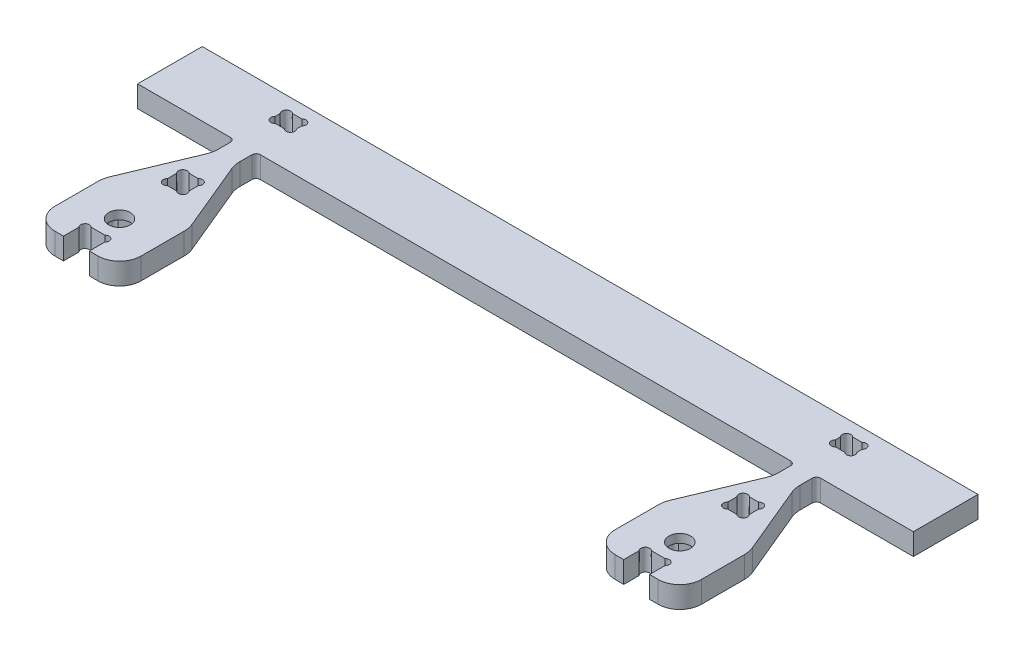
SolidWorks part; units mm, degrees
ref_plane "정면" through (0, 0, 0) normal (0, 0, 1) x (1, 0, 0)
ref_plane "윗면" through (0, 0, 0) normal (0, 1, 0) x (1, 0, 0)
ref_plane "우측면" through (0, 0, 0) normal (1, 0, 0) x (0, 0, -1)
sketch "스케치1" plane through (0, 0, 0) normal (0, 1, 0) x (1, 0, 0)
  line L0 (0, 0) -> (0, 54.2) construction
  line L1 (-90, 54.2) -> (90, 54.2)
  line L2 (90, 54.2) -> (90, 39.2)
  line L3 (90, 39.2) -> (75, 39.2)
  line L4 (75, 39.2) -> (75, 0)
  line L5 (75, 0) -> (55, 0)
  line L6 (55, 0) -> (55, 39.2)
  line L7 (55, 39.2) -> (-55, 39.2)
  line L8 (75, 39.2) -> (55, 39.2) construction
  line L9 (55, 0) -> (0, 0) construction
  line L10 (75, 10) -> (65, 10) construction
  line L11 (65, 10) -> (55, 10) construction
  line L12 (65, 10) -> (65, 0) construction
  line L13 (-65, 10) -> (-65, 0) construction
  line L14 (-65, 10) -> (-55, 10) construction
  line L15 (-75, 10) -> (-65, 10) construction
  line L16 (-75, 39.2) -> (-55, 39.2) construction
  line L17 (-55, 0) -> (-55, 39.2)
  line L18 (-75, 0) -> (-55, 0)
  line L19 (-75, 39.2) -> (-75, 0)
  line L20 (-90, 39.2) -> (-75, 39.2)
  line L21 (-90, 54.2) -> (-90, 39.2)
  circle A0 centre (65, 10) radius 2.5
  circle A1 centre (-65, 10) radius 2.5
  point P16 (0, 39.2)
  dimension "D1" = 5
  dimension "D2" = 65
  dimension "D3" = 39.2
  dimension "D4" = 90
  dimension "D5" = 15
  dimension "D6" = 20
extrude "보스-돌출1" add sketch "스케치1" along normal blind 5
sketch "스케치2" plane through (0, 5, 0) normal (0, 1, 0) x (1, 0, 0)
  line L0 (67.5, 52.6142) -> (67.5, 54.2) construction
  line L1 (75, 39.2) -> (67.5, 39.2)
  line L2 (75, 39.2) -> (75, 35.2)
  line L3 (75, 35.2) -> (67.5, 35.2)
  line L4 (67.5, 39.2) -> (67.5, 35.2)
  line L5 (-67.5, 52.6142) -> (-67.5, 54.2) construction
  line L6 (-75, 39.2) -> (-67.5, 39.2)
  line L7 (-75, 39.2) -> (-75, 35.2)
  line L8 (-75, 35.2) -> (-67.5, 35.2)
  line L9 (-67.5, 39.2) -> (-67.5, 35.2)
  dimension "D1" = 4
extrude "컷-돌출1" [suppressed] cut sketch "스케치2" against normal blind 10
sketch "스케치4" plane through (0, 0, 0) normal (0, -1, 0) x (1, 0, 0)
  line L0 (0, 0) -> (0, -39.2) construction
  line L1 (-55, -39.2) -> (55, -39.2) construction
  line L2 (65, -10) -> (65, -17) construction
  line L3 (-65, -10) -> (-65, -17) construction
  circle A0 centre (65, -10) radius 7 construction
  circle A1 centre (65, -17) radius 1.1
  circle A2 centre (58.9378, -6.5) radius 1.1
  circle A3 centre (71.0622, -6.5) radius 1.1
  circle A5 centre (-65, -10) radius 7 construction
  circle A6 centre (-71.0622, -6.5) radius 1.1
  circle A7 centre (-58.9378, -6.5) radius 1.1
  circle A8 centre (-65, -17) radius 1.1
  point P11 (65, -10)
  point P20 (65, -10)
  dimension "D1" = 2.2
  dimension "D2" = 14
  dimension "D3" = 3
extrude "컷-돌출3" [suppressed] cut sketch "스케치4" against normal blind 10
fillet "필렛1" radius 5 4 edges at (-75, 2.5, 0) (-55, 2.5, 0) (55, 2.5, 0) (75, 2.5, 0)
sketch "스케치6" plane through (0, 0, 0) normal (0, -1, 0) x (1, 0, 0)
  line L0 (60, 0) -> (70, 0) construction
  line L1 (62, 0) -> (68, 0)
  line L2 (62, 0) -> (62, -5)
  line L3 (62, -5) -> (68, -5)
  line L4 (68, 0) -> (68, -5)
  line L5 (0, 0) -> (0, -39.2) construction
  line L6 (-55, -39.2) -> (55, -39.2) construction
  line L7 (-68, 0) -> (-68, -5)
  line L8 (-62, -5) -> (-68, -5)
  line L9 (-62, 0) -> (-62, -5)
  line L10 (-62, 0) -> (-68, 0)
  dimension "D1" = 5
extrude "컷-돌출5" cut sketch "스케치6" against normal blind 10
sketch "스케치7" plane through (0, 0, 0) normal (0, -1, 0) x (1, 0, 0)
  line L0 (62, -5) -> (62.7071, -4.2929) construction
  line L1 (68, -5) -> (67.2929, -4.2929) construction
  line L2 (62, -5) -> (68, -5) construction
  line L3 (62, -5) -> (68, -5) construction
  line L4 (0, 0) -> (0, -39.2) construction
  line L5 (-55, -39.2) -> (55, -39.2) construction
  line L6 (-68, -5) -> (-67.2929, -4.2929) construction
  line L7 (-62, -5) -> (-62.7071, -4.2929) construction
  circle A0 centre (62.7071, -4.2929) radius 1
  circle A1 centre (67.2929, -4.2929) radius 1
  circle A2 centre (-67.2929, -4.2929) radius 1
  circle A3 centre (-62.7071, -4.2929) radius 1
  dimension "D3" = 2
  dimension "D1" = 45
  dimension "D2" = 45
extrude "컷-돌출6" cut sketch "스케치7" against normal blind 10
sketch "스케치8" plane through (0, 5, 0) normal (0, 1, 0) x (1, 0, 0)
  line L0 (67.5, 39.2) -> (62.5, 39.2) construction
  line L1 (75, 39.2) -> (67.5, 39.2)
  line L2 (75, 39.2) -> (75, 34.2)
  line L3 (75, 34.2) -> (67.5, 34.2)
  line L4 (67.5, 39.2) -> (67.5, 34.2)
  line L5 (55, 39.2) -> (62.5, 39.2)
  line L6 (55, 39.2) -> (55, 34.2)
  line L7 (55, 34.2) -> (62.5, 34.2)
  line L8 (62.5, 39.2) -> (62.5, 34.2)
  line L9 (62.5, 34.2) -> (67.5, 34.2) construction
  line L10 (0, 0) -> (0, 39.2) construction
  line L11 (-55, 39.2) -> (55, 39.2) construction
  line L12 (-62.5, 34.2) -> (-67.5, 34.2) construction
  line L13 (-67.5, 39.2) -> (-62.5, 39.2) construction
  line L14 (-62.5, 39.2) -> (-62.5, 34.2)
  line L15 (-55, 34.2) -> (-62.5, 34.2)
  line L16 (-55, 39.2) -> (-55, 34.2)
  line L17 (-55, 39.2) -> (-62.5, 39.2)
  line L18 (-67.5, 39.2) -> (-67.5, 34.2)
  line L19 (-75, 34.2) -> (-67.5, 34.2)
  line L20 (-75, 39.2) -> (-75, 34.2)
  line L21 (-75, 39.2) -> (-67.5, 39.2)
  dimension "D1" = 5
  dimension "D2" = 5
extrude "컷-돌출7" cut sketch "스케치8" against normal blind 10
fillet "필렛2" radius 1 4 edges at (-67.5, 2.5, -39.2) (-62.5, 2.5, -39.2) (62.5, 2.5, -39.2) (67.5, 2.5, -39.2)
sketch "스케치10" plane through (0, 5, 0) normal (0, 1, 0) x (1, 0, 0)
  line L0 (75, 16.2) -> (55, 16.2) construction
  line L2 (75, 5) -> (75, 34.2) construction
  line L3 (75, 34.2) -> (67.5, 34.2)
  line L4 (62.5, 34.2) -> (55, 34.2)
  line L5 (55, 34.2) -> (55, 5) construction
  line L6 (0, 0) -> (0, 39.2) construction
  line L7 (-61.5, 39.2) -> (61.5, 39.2) construction
  line L8 (62.5, 34.2) -> (55, 16.2)
  line L9 (55, 16.2) -> (55, 34.2)
  line L10 (67.5, 34.2) -> (75, 16.2)
  line L11 (75, 16.2) -> (75, 34.2)
  line L12 (-75, 16.2) -> (-55, 16.2) construction
  line L13 (-75, 16.2) -> (-75, 34.2)
  line L14 (-67.5, 34.2) -> (-75, 16.2)
  line L15 (-55, 16.2) -> (-55, 34.2)
  line L16 (-62.5, 34.2) -> (-55, 16.2)
  line L17 (-62.5, 34.2) -> (-55, 34.2)
  line L18 (-75, 34.2) -> (-67.5, 34.2)
  dimension "D1" = 18
extrude "컷-돌출9" cut sketch "스케치10" against normal blind 10
fillet "필렛3" radius 6 8 edges at (-55, 2.5, -16.2) (-75, 2.5, -16.2) (55, 2.5, -16.2) (75, 2.5, -16.2) (-67.5, 2.5, -34.2) (-62.5, 2.5, -34.2) (62.5, 2.5, -34.2) (67.5, 2.5, -34.2)
sketch "스케치12" plane through (0, 5, 0) normal (0, 1, 0) x (1, 0, 0)
  line L0 (0, 0) -> (0, 39.2) construction
  line L1 (62.5, 47.2) -> (67.5, 47.2)
  line L2 (62.5, 47.2) -> (62.5, 51.2)
  line L3 (62.5, 51.2) -> (67.5, 51.2)
  line L4 (67.5, 47.2) -> (67.5, 51.2)
  line L5 (62.5, 27.2) -> (67.5, 27.2)
  line L6 (62.5, 27.2) -> (62.5, 22.2)
  line L7 (62.5, 22.2) -> (67.5, 22.2)
  line L8 (67.5, 27.2) -> (67.5, 22.2)
  line L9 (-61.5, 39.2) -> (61.5, 39.2) construction
  line L10 (-67.5, 27.2) -> (-67.5, 22.2)
  line L11 (-62.5, 22.2) -> (-67.5, 22.2)
  line L12 (-62.5, 27.2) -> (-62.5, 22.2)
  line L13 (-62.5, 27.2) -> (-67.5, 27.2)
  line L14 (-67.5, 47.2) -> (-67.5, 51.2)
  line L15 (-62.5, 51.2) -> (-67.5, 51.2)
  line L16 (-62.5, 47.2) -> (-62.5, 51.2)
  line L17 (-62.5, 47.2) -> (-67.5, 47.2)
  line L18 (90, 54.2) -> (-90, 54.2) construction
  line L19 (62.5, 36.8) -> (67.5, 36.8) construction
  line L20 (62.5, 38.2) -> (62.5, 35.4) construction
  line L21 (67.5, 35.4) -> (67.5, 38.2) construction
  line L22 (65, 36.8) -> (65, 47.2) construction
  line L23 (65, 36.8) -> (65, 27.2) construction
  dimension "D1" = 3
  dimension "D2" = 4
  dimension "D3" = 20
  dimension "D4" = 5
  dimension "D5" = 5
extrude "컷-돌출10" cut sketch "스케치12" against normal blind 5
sketch "스케치14" plane through (0, 0, 0) normal (0, -1, 0) x (-1, 0, 0)
  line L1 (-65, 14.6188) -> (-69, 12.3094)
  line L2 (-69, 12.3094) -> (-69, 7.6906)
  line L3 (-69, 7.6906) -> (-65, 5.3812)
  line L4 (-65, 5.3812) -> (-61, 7.6906)
  line L5 (-61, 7.6906) -> (-61, 12.3094)
  line L6 (-61, 12.3094) -> (-65, 14.6188)
  line L7 (65, 14.6188) -> (61, 12.3094)
  line L8 (61, 12.3094) -> (61, 7.6906)
  line L9 (61, 7.6906) -> (65, 5.3812)
  line L10 (65, 5.3812) -> (69, 7.6906)
  line L11 (69, 7.6906) -> (69, 12.3094)
  line L12 (69, 12.3094) -> (65, 14.6188)
  circle A0 centre (-65, 10) radius 4 construction
  circle A1 centre (65, 10) radius 4 construction
  dimension "D1" = 8
  dimension "D2" = 8
extrude "컷-돌출12" cut sketch "스케치14" against normal blind 3
sketch "스케치15" plane through (0, 0, 0) normal (0, -1, 0) x (1, 0, 0)
  line L0 (65, -13.6188) -> (65, -14.6188) construction
  line L1 (0, 0) -> (0, -39.2) construction
  line L2 (-61.5, -39.2) -> (61.5, -39.2) construction
  line L3 (-65, -13.6188) -> (-65, -14.6188) construction
  circle A0 centre (65, -13.6188) radius 1
  circle A1 centre (61.866, -11.8094) radius 1
  circle A2 centre (61.866, -8.1906) radius 1
  circle A3 centre (65, -6.3812) radius 1
  circle A4 centre (68.134, -8.1906) radius 1
  circle A5 centre (68.134, -11.8094) radius 1
  circle A6 centre (-68.134, -11.8094) radius 1
  circle A7 centre (-68.134, -8.1906) radius 1
  circle A8 centre (-65, -6.3812) radius 1
  circle A9 centre (-61.866, -8.1906) radius 1
  circle A10 centre (-61.866, -11.8094) radius 1
  circle A11 centre (-65, -13.6188) radius 1
  point P3 (65, -10)
  point P19 (65, -10)
  point P35 (-65, -10)
  dimension "D1" = 2
  dimension "D2" = 6
extrude "컷-돌출13" cut sketch "스케치15" against normal blind 3
sketch "스케치16" plane through (0, 0, 0) normal (0, -1, 0) x (1, 0, 0)
  line L0 (0, -39.2) -> (0, 0) construction
  line L1 (-61.5, -39.2) -> (61.5, -39.2) construction
  line L2 (66.7809, -22.9191) -> (67.5, -22.2) construction
  line L3 (62.5, -47.2) -> (67.5, -47.2) construction
  line L5 (63.2191, -22.9191) -> (62.5, -22.2) construction
  line L6 (66.7929, -47.9071) -> (67.5, -47.2) construction
  line L7 (66.7929, -50.4929) -> (67.5, -51.2) construction
  line L8 (63.2071, -50.4929) -> (62.5, -51.2) construction
  line L9 (63.2071, -47.9071) -> (62.5, -47.2) construction
  line L10 (67.5, -51.2) -> (62.5, -51.2) construction
  line L11 (63.2191, -26.4809) -> (62.5, -27.2) construction
  line L12 (66.7809, -26.4809) -> (67.5, -27.2) construction
  line L13 (62.5, -22.2) -> (67.5, -22.2) construction
  line L14 (67.5, -27.2) -> (62.5, -27.2) construction
  line L15 (-66.7809, -26.4809) -> (-67.5, -27.2) construction
  line L16 (-63.2191, -26.4809) -> (-62.5, -27.2) construction
  line L18 (-63.2071, -47.9071) -> (-62.5, -47.2) construction
  line L20 (-63.2071, -50.4929) -> (-62.5, -51.2) construction
  line L22 (-66.7929, -50.4929) -> (-67.5, -51.2) construction
  line L23 (-66.7929, -47.9071) -> (-67.5, -47.2) construction
  line L24 (-63.2191, -22.9191) -> (-62.5, -22.2) construction
  line L25 (-66.7809, -22.9191) -> (-67.5, -22.2) construction
  circle A0 centre (66.7929, -47.9071) radius 1
  circle A1 centre (66.7929, -50.4929) radius 1
  circle A2 centre (63.2071, -50.4929) radius 1
  circle A3 centre (63.2071, -47.9071) radius 1
  circle A4 centre (66.7809, -22.9191) radius 1.017
  circle A5 centre (63.2191, -22.9191) radius 1.017
  circle A6 centre (63.2191, -26.4809) radius 1.017
  circle A7 centre (66.7809, -26.4809) radius 1.017
  circle A8 centre (-66.7809, -26.4809) radius 1.017
  circle A9 centre (-63.2191, -26.4809) radius 1.017
  circle A10 centre (-63.2191, -22.9191) radius 1.017
  circle A11 centre (-66.7809, -22.9191) radius 1.017
  circle A12 centre (-63.2071, -47.9071) radius 1
  circle A13 centre (-63.2071, -50.4929) radius 1
  circle A14 centre (-66.7929, -50.4929) radius 1
  circle A15 centre (-66.7929, -47.9071) radius 1
  dimension "D5" = 2
  dimension "D1" = 45
  dimension "D2" = 45
  dimension "D3" = 45
  dimension "D4" = 45
  dimension "D6" = 45
  dimension "D7" = 45
  dimension "D8" = 45
  dimension "D9" = 45
extrude "컷-돌출14" cut sketch "스케치16" against normal blind 10
